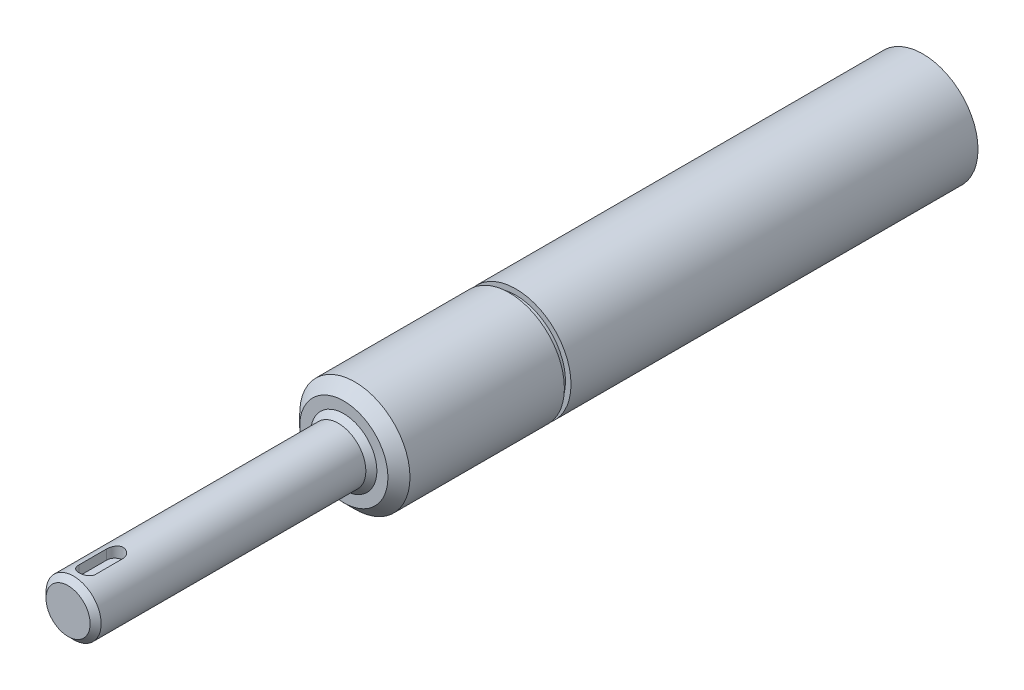
SolidWorks part; units mm, degrees
ref_plane "Płaszczyzna przednia" through (0, 0, 0) normal (0, 0, 1) x (1, 0, 0)
ref_plane "Płaszczyzna górna" through (0, 0, 0) normal (0, 1, 0) x (1, 0, 0)
ref_plane "Płaszczyzna prawa" through (0, 0, 0) normal (1, 0, 0) x (0, 0, -1)
sketch "Szkic1" plane through (0, 0, 0) normal (0, 0, 1) x (1, 0, 0)
  circle A0 centre (0, 0) radius 10
  dimension "D1" = 20
extrude "Dodanie-wyciągnięcie1" add sketch "Szkic1" along normal blind 105
sketch "Szkic2" plane through (0, 0, 105) normal (0, 0, 1) x (1, 0, 0)
  circle A0 centre (0, 0) radius 5
  dimension "D1" = 10
extrude "Dodanie-wyciągnięcie2" add sketch "Szkic2" along normal blind 50 contours A0
ref_plane "Płaszczyzna1" through (0, 5, 0) normal (0, 1, 0) x (1, 0, 0)
sketch "Szkic3" plane through (0, 5, 0) normal (0, 1, 0) x (1, 0, 0)
  line L0 (0, -105) -> (0, -155)
  line L1 (0, -105) -> (0, -155)
  line L2 (0, -151.5) -> (0, -146.5) construction
  line L7 (-1.5, -151.5) -> (-1.5, -146.5)
  line L8 (1.5, -151.5) -> (1.5, -146.5)
  line L9 (-5, -155) -> (5, -155) construction
  arc A4 (-1.5, -151.5) -> (1.5, -151.5) centre (0, -151.5) ccw
  arc A5 (1.5, -146.5) -> (-1.5, -146.5) centre (0, -146.5) ccw
  point P4 (0, -149)
  point P9 (0, -145)
  point P10 (0, -153)
  dimension "D1" = 3
  dimension "D2" = 8
  dimension "D3" = 2
extrude "Wytnij-wyciągnięcie1" cut sketch "Szkic3" against normal blind 2 contours L7 A5 L8 A4
chamfer "Sfazowanie1" distance 1 angle 45 1 edges at (5, 0, 105)
chamfer "Sfazowanie2" distance 2 angle 45 1 edges at (10, 0, 105)
chamfer "Sfazowanie3" distance 1 angle 45 1 edges at (5, 0, 155)
sketch "Szkic5" plane through (0, 0, 0) normal (0, 1, 0) x (1, 0, 0)
  line L0 (5, -106) -> (5, -154)
  line L1 (5, -154) -> (4, -155)
  line L2 (4, -155) -> (-4, -155)
  line L3 (-4, -155) -> (-5, -154)
  line L4 (-5, -154) -> (-5, -106)
  line L5 (-5, -106) -> (-6, -105)
  line L6 (-6, -105) -> (-8, -105)
  line L7 (-8, -105) -> (-10, -103)
  line L8 (-10, -103) -> (-10, 0)
  line L9 (-10, 0) -> (10, 0)
  line L10 (10, 0) -> (10, -103)
  line L11 (10, -103) -> (8, -105)
  line L12 (8, -105) -> (6, -105)
  line L13 (6, -105) -> (5, -106)
  line L14 (-10, -75) -> (-9, -75)
  line L15 (-9, -75) -> (-9, -73.8)
  line L16 (-9, -73.8) -> (-10, -73.8)
  line L17 (-10, -73.8) -> (-10, -75)
  line L18 (0, -106) -> (0, 49894) construction
  line L19 (5, -106) -> (-5, -106) construction
  point P14 (5.5, -105.5)
  point P15 (7, -105)
  point P24 (0, -106)
  dimension "D1" = 1
  dimension "D2" = 1.2
  dimension "D3" = 30
revolve "Wycięcie-obrót1" cut sketch "Szkic5" angle 360 about L18
